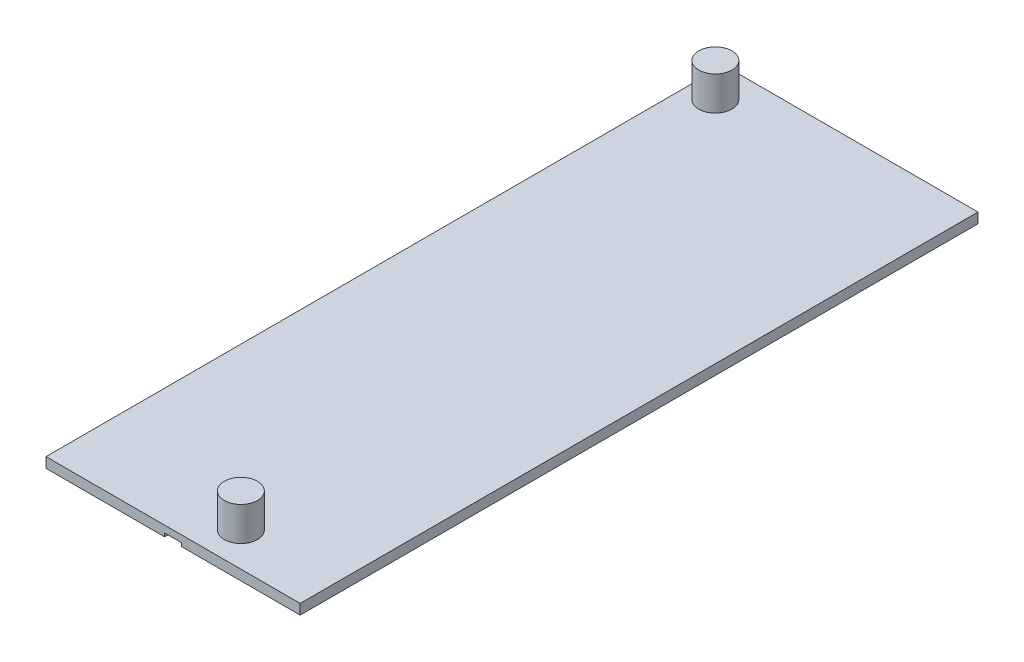
SolidWorks part; units mm, degrees
ref_plane "Front Plane" through (0, 0, 0) normal (0, 0, 1) x (1, 0, 0)
ref_plane "Top Plane" through (0, 0, 0) normal (0, 1, 0) x (1, 0, 0)
ref_plane "Right Plane" through (0, 0, 0) normal (1, 0, 0) x (0, 0, -1)
sketch "Sketch1" plane through (0, 0, 0) normal (0, 0, 1) x (1, 0, 0)
  line L1 (0, 0) -> (75, 0)
  line L2 (0, 0) -> (0, 3)
  line L3 (0, 3) -> (75, 3)
  line L4 (75, 0) -> (75, 3)
  dimension "D1" = 3
  dimension "D2" = 75
extrude "Boss-Extrude1" add sketch "Sketch1" along normal blind 200
sketch "Sketch2" plane through (0, 3, 0) normal (0, 1, 0) x (1, 0, 0)
  line L1 (150, 0) -> (-75, 0)
  line L2 (150, 0) -> (150, -200)
  line L3 (150, -200) -> (-75, -200)
  line L4 (-75, 0) -> (-75, -200)
  line L5 (137.5, -200) -> (-62.5, -200)
  line L6 (137.5, -200) -> (137.5, 0)
  line L7 (137.5, 0) -> (-62.5, 0)
  line L8 (-62.5, -200) -> (-62.5, 0)
  line L9 (75, -200) -> (0, -200) construction
  line L10 (75, 0) -> (0, 0) construction
  line L11 (75, -200) -> (75, 0) construction
  circle A0 centre (127.5, -190) radius 4.9
  circle A1 centre (87.5, -10) radius 4.9
  circle A2 centre (47.5, -190) radius 4.9
  circle A3 centre (7.5, -10) radius 4.9
  dimension "D4" = 10
  dimension "D5" = 10
  dimension "D6" = 9.8
  dimension "D7" = 9.8
  dimension "D8" = 10
  dimension "D9" = 40
  dimension "D11" = 10
  dimension "D12" = 10
  dimension "D13" = 80
  dimension "D14" = 80
  dimension "D15" = 9.8
  dimension "D16" = 9.8
  dimension "D1" = 225
  dimension "D2" = 12.5
  dimension "D3" = 12.5
  dimension "D10" = 75
extrude "Boss-Extrude2" add sketch "Sketch2" along normal blind 10 contours A3 | A2
sketch "Sketch3" plane through (0, 0, 0) normal (0, -1, 0) x (1, 0, 0)
  line L0 (0, 200) -> (75, 200) construction
  line L1 (35, 200) -> (40, 200)
  line L2 (35, 200) -> (35, 81)
  line L3 (35, 81) -> (40, 81)
  line L4 (40, 200) -> (40, 81)
  line L7 (0, 0) -> (75, 0) construction
  point P8 (37.5, 200)
  point P9 (37.5, 200)
  point P10 (0, 0)
  dimension "D1" = 5
  dimension "D2" = 81
extrude "Cut-Extrude1" cut sketch "Sketch3" against normal blind 1
sketch "Sketch4" plane through (0, 0, 0) normal (0, -1, 0) x (1, 0, 0)
  line L0 (4, 43) -> (11, 43)
  line L1 (4, 43) -> (4, 10)
  line L2 (4, 10) -> (11, 10)
  line L3 (11, 43) -> (11, 10)
  line L4 (4, 47) -> (11, 47)
  line L5 (4, 47) -> (4, 80)
  line L6 (4, 80) -> (11, 80)
  line L7 (11, 47) -> (11, 80)
  line L40 (0, 200) -> (0, 0) construction
  line L42 (19, 43) -> (26, 43)
  line L43 (19, 43) -> (19, 10)
  line L44 (19, 10) -> (26, 10)
  line L45 (26, 43) -> (26, 10)
  line L46 (19, 47) -> (26, 47)
  line L47 (19, 47) -> (19, 80)
  line L48 (19, 80) -> (26, 80)
  line L49 (26, 47) -> (26, 80)
  line L50 (34, 43) -> (41, 43)
  line L51 (34, 43) -> (34, 10)
  line L52 (34, 10) -> (41, 10)
  line L53 (41, 43) -> (41, 10)
  line L54 (34, 47) -> (41, 47)
  line L55 (34, 47) -> (34, 80)
  line L56 (34, 80) -> (41, 80)
  line L57 (41, 47) -> (41, 80)
  line L58 (49, 43) -> (56, 43)
  line L59 (49, 43) -> (49, 10)
  line L60 (49, 10) -> (56, 10)
  line L61 (56, 43) -> (56, 10)
  line L62 (49, 47) -> (56, 47)
  line L63 (49, 47) -> (49, 80)
  line L64 (49, 80) -> (56, 80)
  line L65 (56, 47) -> (56, 80)
  line L66 (64, 43) -> (71, 43)
  line L67 (64, 43) -> (64, 10)
  line L68 (64, 10) -> (71, 10)
  line L69 (71, 43) -> (71, 10)
  line L70 (64, 47) -> (71, 47)
  line L71 (64, 47) -> (64, 80)
  line L72 (64, 80) -> (71, 80)
  line L73 (71, 47) -> (71, 80)
  line L74 (0, 0) -> (75, 0) construction
  dimension "D1" = 70
  dimension "D2" = 33
  dimension "D3" = 33
  dimension "D4" = 7
  dimension "D5" = 7
  dimension "D6" = 4
  dimension "D8" = 10
  dimension "D7" = 5
extrude "Cut-Extrude2" cut sketch "Sketch4" against normal blind 1
